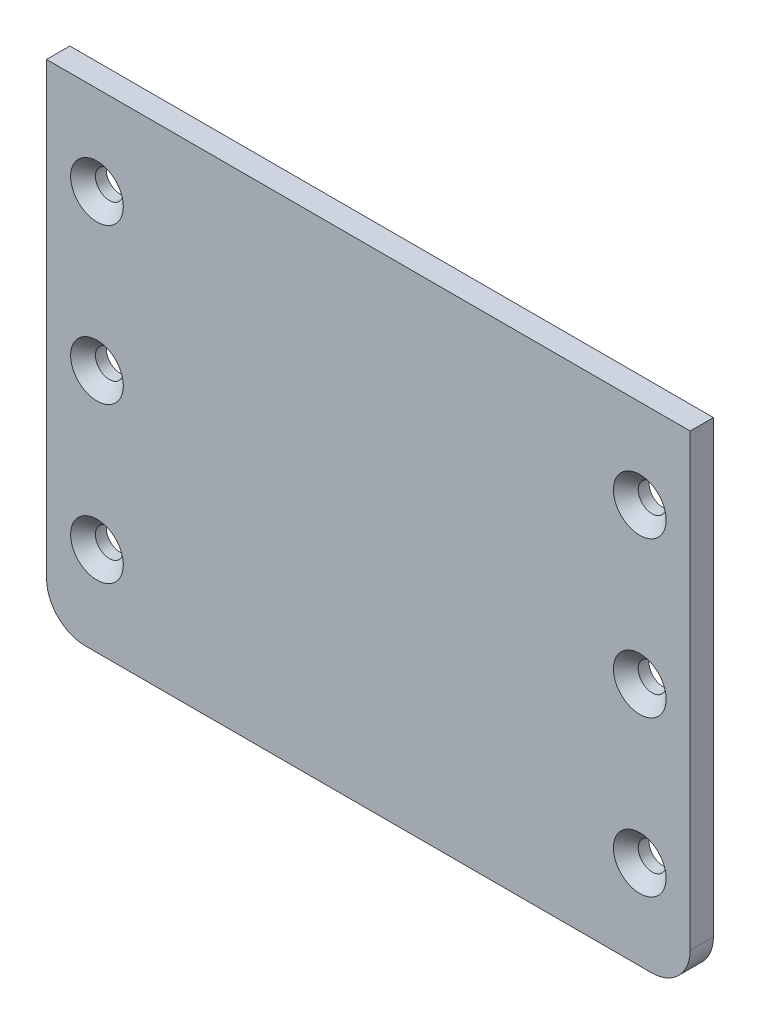
SolidWorks part; units mm, degrees
ref_plane "Front Plane" through (0, 0, 0) normal (0, 0, 1) x (1, 0, 0)
ref_plane "Top Plane" through (0, 0, 0) normal (0, 1, 0) x (1, 0, 0)
ref_plane "Right Plane" through (0, 0, 0) normal (1, 0, 0) x (0, 0, -1)
sketch "Sketch1" plane through (0, 0, 0) normal (0, 0, 1) x (1, 0, 0)
  line L1 (0, 0) -> (11, 0)
  line L2 (0, 0) -> (0, 63)
  line L3 (0, 63) -> (11, 63)
  line L4 (11, 0) -> (11, 63)
  line L5 (0, 0) -> (-61, 0)
  line L6 (0, 0) -> (0, 63)
  line L7 (0, 63) -> (-61, 63)
  line L8 (-61, 0) -> (-61, 63)
  line L9 (-61, 0) -> (-72, 0)
  line L10 (-61, 0) -> (-61, 63)
  line L11 (-61, 63) -> (-72, 63)
  line L12 (-72, 0) -> (-72, 63)
  line L13 (0, 0) -> (-60, 0)
  line L14 (0, 0) -> (0, 60)
  line L15 (0, 60) -> (-60, 60)
  line L16 (-60, 0) -> (-60, 60)
  dimension "D1" = 63
  dimension "D2" = 11
  dimension "D3" = 11
  dimension "D4" = 60
  dimension "D5" = 60
  dimension "D6" = 1
extrude "Boss-Extrude1" add sketch "Sketch1" along normal blind 3 contours L12 L9 L8 L11 | L5 L16 L15 L6 L7 L8 | L16 L5 L2 L15 | L1 L4 L3 L6 L2
hole_wizard "CSK for M3 Flat Head Machine Screw1" positions "Sketch2" profile "Sketch3" countersink size "M3" standard "ANSI Metric"
sketch "Sketch2" plane through (0, 0, 3) normal (0, 0, 1) x (1, 0, 0)
  line L0 (-72, 0) -> (-72, 63) construction
  line L1 (11, 0) -> (11, 63) construction
  line L2 (-72, 0) -> (-72, 63) construction
  point P0 (-65.5, 31.5)
  point P2 (-65.5, 51.5)
  point P4 (-65.5, 11.5)
  point P6 (4.5, 11.5)
  point P8 (4.5, 31.5)
  point P10 (4.5, 51.5)
  point P37 (-72, 31.5)
  dimension "D1" = 6.5
  dimension "D2" = 6.5
  dimension "D3" = 20
  dimension "D4" = 20
  dimension "D5" = 20
  dimension "D6" = 20
sketch "Sketch3" plane through (-65.5, 31.5, 3) normal (1, 0, 0) x (0, -1, 0)
  line L0 (0, 0) -> (0, 7.0815)
  line L1 (0, 7.0815) -> (1.8, 6)
  line L2 (1.8, 6) -> (1.8, 1.6)
  line L3 (1.8, 1.6) -> (3.4, 0)
  line L5 (3.4, 0) -> (0, 0)
  line L6 (-1.8, 1.6) -> (-3.4, 0) construction
  line L10 (0, 7.0815) -> (-1.8, 6) construction
  line L11 (0, -6.35) -> (0, 107.95) construction
  dimension "Hole Dia." = 3.6
  dimension "Hole Depth" = 6
  dimension "Near C'Sink Dia." = 6.8
  dimension "Near C'Sink Angle" = 90
  dimension "Drill Angle" = 118
fillet "Fillet1" radius 5 2 edges at (-72, 0, 1.5) (11, 0, 1.5)
